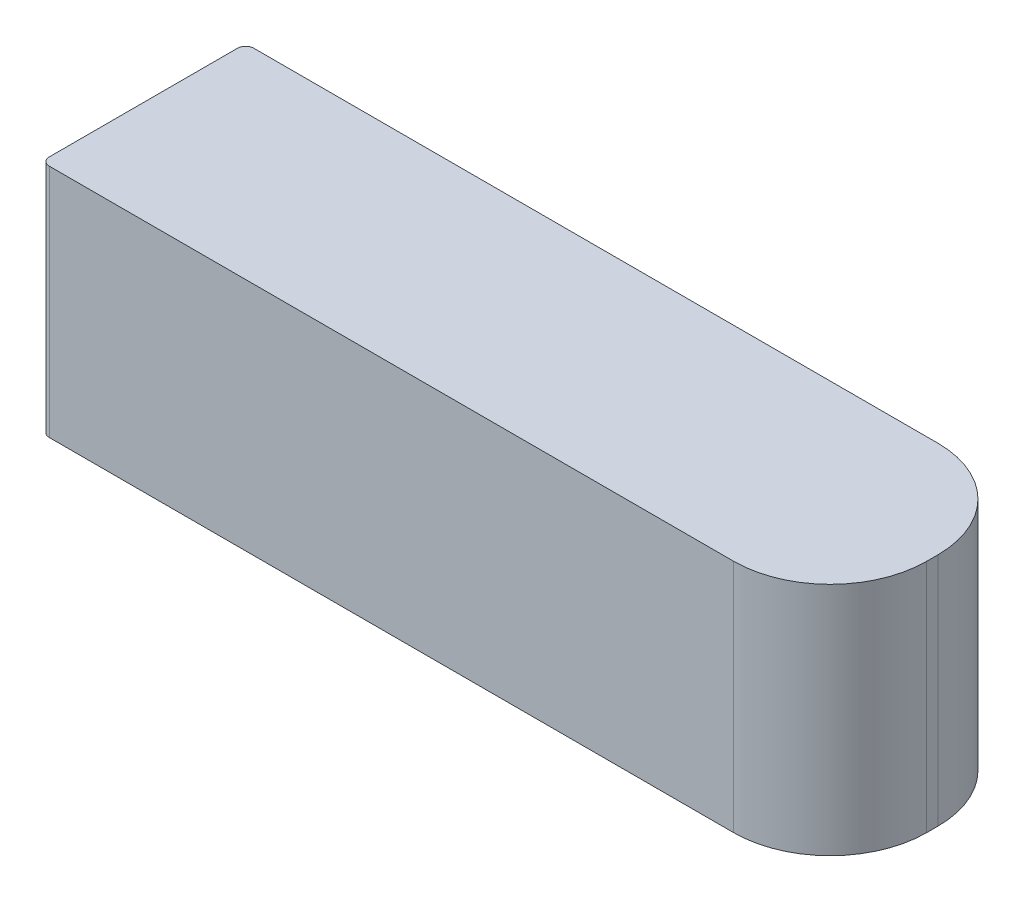
SolidWorks part; units mm, degrees
ref_plane "Front Plane" through (0, 0, 0) normal (0, 0, 1) x (1, 0, 0)
ref_plane "Top Plane" through (0, 0, 0) normal (0, 1, 0) x (1, 0, 0)
ref_plane "Right Plane" through (0, 0, 0) normal (1, 0, 0) x (0, 0, -1)
sketch "Sketch1" plane through (0, 0, 0) normal (0, 1, 0) x (1, 0, 0)
  line L1 (-49.022, -12.7) -> (49.022, -12.7)
  line L2 (-49.022, -12.7) -> (-49.022, 12.7)
  line L3 (-49.022, 12.7) -> (49.022, 12.7)
  line L4 (49.022, -12.7) -> (49.022, 12.7)
  line L5 (-49.022, -12.7) -> (49.022, 12.7) construction
  line L6 (-49.022, 12.7) -> (49.022, -12.7) construction
  point P0 (0, 0)
  dimension "D1" = 98.044
  dimension "D2" = 25.4
extrude "Boss-Extrude1" add sketch "Sketch1" along normal blind 29.21
fillet "Fillet1" radius 12 2 edges at (49.022, 14.605, 12.7) (49.022, 14.605, -12.7)
fillet "Fillet2" radius 1 2 edges at (-49.022, 14.605, 12.7) (-49.022, 14.605, -12.7)
